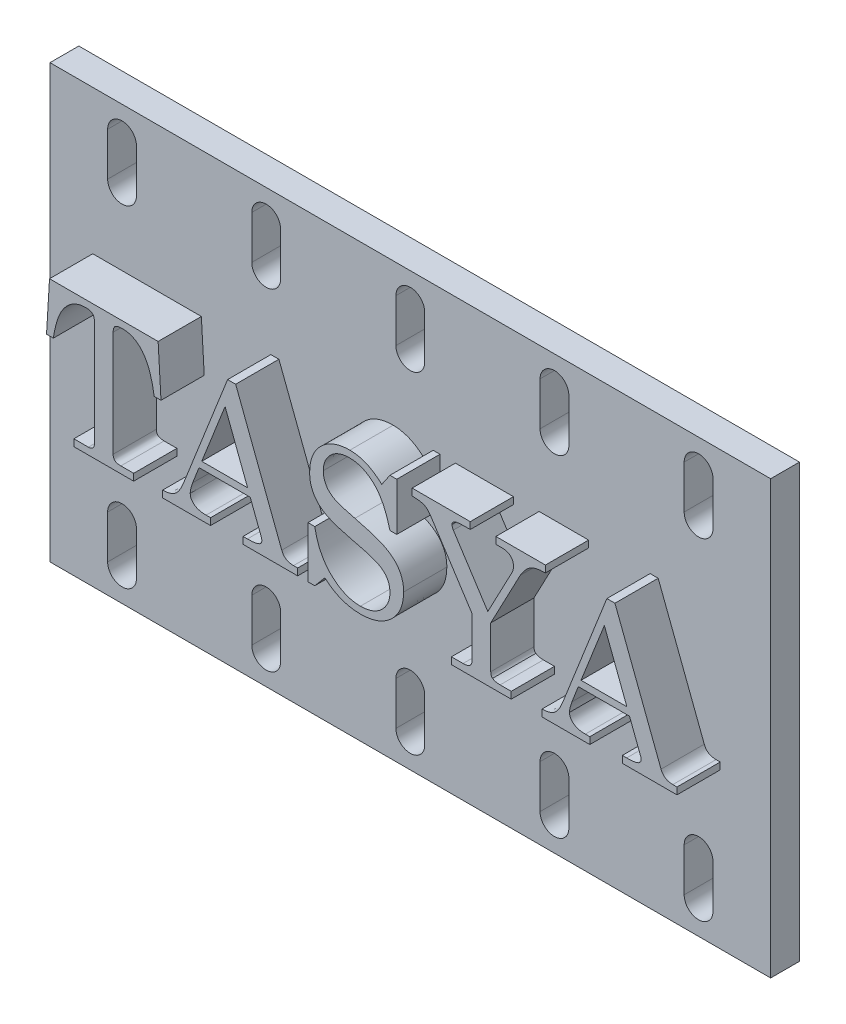
SolidWorks part; units mm, degrees
ref_plane "Front Plane" through (0, 0, 0) normal (0, 0, 1) x (1, 0, 0)
ref_plane "Top Plane" through (0, 0, 0) normal (0, 1, 0) x (1, 0, 0)
ref_plane "Right Plane" through (0, 0, 0) normal (1, 0, 0) x (0, 0, -1)
sketch "Sketch1" plane through (0, 0, 0) normal (0, 0, 1) x (1, 0, 0)
  text T0 "TASYA" font "Century Schoolbook" height in points 36
extrude "Boss-Extrude1" add sketch "Sketch1" along normal blind 5
sketch "Sketch2" plane through (0, 0, 0) normal (0, 0, 1) x (1, 0, 0)
  line L0 (0.5631, 9.2459) -> (8.0976, 9.2459) construction
  line L1 (-2.4039, -10.7541) -> (47.5961, -10.7541)
  line L2 (-2.4039, -10.7541) -> (-2.4039, 19.2459)
  line L3 (-2.4039, 19.2459) -> (47.5961, 19.2459)
  line L4 (47.5961, -10.7541) -> (47.5961, 19.2459)
  line L5 (2.5961, 17.2459) -> (2.5961, 14.2459) construction
  line L6 (3.5961, 17.2459) -> (3.5961, 14.2459)
  line L7 (1.5961, 17.2459) -> (1.5961, 14.2459)
  line L8 (7.5961, 19.2459) -> (7.5961, -10.7541) construction
  line L9 (17.5961, 19.2459) -> (17.5961, -10.7541) construction
  line L10 (27.5961, 19.2459) -> (27.5961, -10.7541) construction
  line L11 (37.5961, 19.2459) -> (37.5961, -10.7541)
  line L12 (-2.4039, 4.2459) -> (47.5961, 4.2459) construction
  line L13 (12.5961, 17.2459) -> (12.5961, 14.2459) construction
  line L14 (11.5961, 17.2459) -> (11.5961, 14.2459)
  line L15 (13.5961, 17.2459) -> (13.5961, 14.2459)
  line L16 (22.5961, 17.2459) -> (22.5961, 14.2459) construction
  line L17 (23.5961, 17.2459) -> (23.5961, 14.2459)
  line L18 (21.5961, 17.2459) -> (21.5961, 14.2459)
  line L19 (32.5961, 17.2459) -> (32.5961, 14.2459) construction
  line L20 (31.5961, 17.2459) -> (31.5961, 14.2459)
  line L21 (33.5961, 17.2459) -> (33.5961, 14.2459)
  line L22 (42.5961, 17.2459) -> (42.5961, 14.2459) construction
  line L23 (43.5961, 17.2459) -> (43.5961, 14.2459)
  line L24 (41.5961, 17.2459) -> (41.5961, 14.2459)
  line L25 (2.5961, -8.7541) -> (2.5961, -5.7541) construction
  line L26 (3.5961, -8.7541) -> (3.5961, -5.7541)
  line L27 (1.5961, -8.7541) -> (1.5961, -5.7541)
  line L28 (12.5961, -8.7541) -> (12.5961, -5.7541) construction
  line L29 (11.5961, -8.7541) -> (11.5961, -5.7541)
  line L30 (13.5961, -8.7541) -> (13.5961, -5.7541)
  line L31 (22.5961, -8.7541) -> (22.5961, -5.7541) construction
  line L32 (23.5961, -8.7541) -> (23.5961, -5.7541)
  line L33 (21.5961, -8.7541) -> (21.5961, -5.7541)
  line L34 (32.5961, -8.7541) -> (32.5961, -5.7541) construction
  line L35 (31.5961, -8.7541) -> (31.5961, -5.7541)
  line L36 (33.5961, -8.7541) -> (33.5961, -5.7541)
  line L37 (42.5961, -8.7541) -> (42.5961, -5.7541) construction
  line L38 (43.5961, -8.7541) -> (43.5961, -5.7541)
  line L39 (41.5961, -8.7541) -> (41.5961, -5.7541)
  arc A0 (3.5961, 17.2459) -> (1.5961, 17.2459) centre (2.5961, 17.2459) ccw
  arc A1 (1.5961, 14.2459) -> (3.5961, 14.2459) centre (2.5961, 14.2459) ccw
  arc A2 (11.5961, 17.2459) -> (13.5961, 17.2459) centre (12.5961, 17.2459) cw
  arc A3 (13.5961, 14.2459) -> (11.5961, 14.2459) centre (12.5961, 14.2459) cw
  arc A4 (23.5961, 17.2459) -> (21.5961, 17.2459) centre (22.5961, 17.2459) ccw
  arc A5 (21.5961, 14.2459) -> (23.5961, 14.2459) centre (22.5961, 14.2459) ccw
  arc A6 (31.5961, 17.2459) -> (33.5961, 17.2459) centre (32.5961, 17.2459) cw
  arc A7 (33.5961, 14.2459) -> (31.5961, 14.2459) centre (32.5961, 14.2459) cw
  arc A8 (43.5961, 17.2459) -> (41.5961, 17.2459) centre (42.5961, 17.2459) ccw
  arc A9 (41.5961, 14.2459) -> (43.5961, 14.2459) centre (42.5961, 14.2459) ccw
  arc A10 (3.5961, -8.7541) -> (1.5961, -8.7541) centre (2.5961, -8.7541) cw
  arc A11 (1.5961, -5.7541) -> (3.5961, -5.7541) centre (2.5961, -5.7541) cw
  arc A12 (11.5961, -8.7541) -> (13.5961, -8.7541) centre (12.5961, -8.7541) ccw
  arc A13 (13.5961, -5.7541) -> (11.5961, -5.7541) centre (12.5961, -5.7541) ccw
  arc A14 (23.5961, -8.7541) -> (21.5961, -8.7541) centre (22.5961, -8.7541) cw
  arc A15 (21.5961, -5.7541) -> (23.5961, -5.7541) centre (22.5961, -5.7541) cw
  arc A16 (31.5961, -8.7541) -> (33.5961, -8.7541) centre (32.5961, -8.7541) ccw
  arc A17 (33.5961, -5.7541) -> (31.5961, -5.7541) centre (32.5961, -5.7541) ccw
  arc A18 (43.5961, -8.7541) -> (41.5961, -8.7541) centre (42.5961, -8.7541) cw
  arc A19 (41.5961, -5.7541) -> (43.5961, -5.7541) centre (42.5961, -5.7541) cw
  point P9 (2.5961, 15.7459)
  point P27 (12.5961, 15.7459)
  point P34 (22.5961, 15.7459)
  point P41 (32.5961, 15.7459)
  point P48 (42.5961, 15.7459)
  point P55 (2.5961, -7.2541)
  point P62 (12.5961, -7.2541)
  point P69 (22.5961, -7.2541)
  point P76 (32.5961, -7.2541)
  point P83 (42.5961, -7.2541)
  dimension "D6" = 1
  dimension "D8" = 2
  dimension "D1" = 30
  dimension "D2" = 50
  dimension "D3" = 10
  dimension "D4" = 3.5
  dimension "D5" = 3
  dimension "D7" = 4
  dimension "D9" = 10
  dimension "D10" = 10
  dimension "D11" = 10
  dimension "D12" = 10
extrude "Boss-Extrude3" add sketch "Sketch2" along normal blind 2 contours L11 L3 L2 L1 A17 L36 A16 L35 A13 L30 A12 L29 A5 L18 A4 L17 A1 L7 A0 L6 L15 A3 L14 A2 L21 A7 L20 A6 L27 A11 L26 A10 L33 A15 L32 A14 | L3 L11 L1 L4 A9 L24 A8 L23 L39 A19 L38 A18
